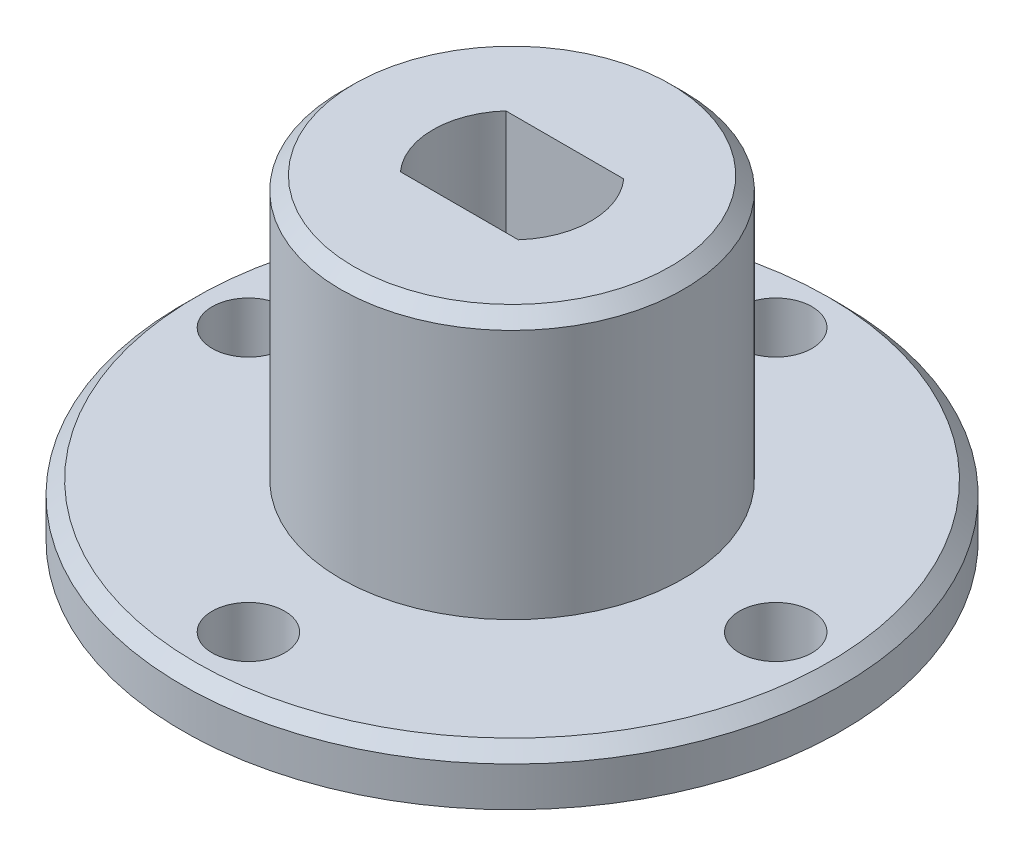
SolidWorks part; units mm, degrees
material "6061 Legierung"
ref_plane "Ebene vorne" through (0, 0, 0) normal (0, 0, 1) x (1, 0, 0)
ref_plane "Ebene oben" through (0, 0, 0) normal (0, 1, 0) x (1, 0, 0)
ref_plane "Ebene rechts" through (0, 0, 0) normal (1, 0, 0) x (0, 0, -1)
sketch "Skizze1" plane through (0, 0, 0) normal (0, 1, 0) x (1, 0, 0)
  line L0 (-4.4721, 4) -> (4.4721, 4)
  line L1 (-4.4721, -4) -> (4.4721, -4)
  circle A0 centre (0, 0) radius 13
  arc A1 (-4.4721, 4) -> (-4.4721, -4) centre (0, 0) ccw
  arc A2 (4.4721, -4) -> (4.4721, 4) centre (0, 0) ccw
  dimension "D1" = 26
  dimension "D2" = 12
  dimension "D3" = 8
  dimension "D4" = 4
extrude "Aufsatz-Linear austragen1" add sketch "Skizze1" along normal blind 20
sketch "Skizze5" plane through (0, 0, 0) normal (0, -1, 0) x (1, 0, 0)
  line L0 (4.4721, -4) -> (-4.4721, -4) construction
  line L1 (-4.4721, 4) -> (4.4721, 4) construction
  line L2 (4.4721, -4) -> (-4.4721, -4)
  line L3 (-4.4721, 4) -> (4.4721, 4)
  circle A0 centre (0, 0) radius 25
  arc A3 (4.4721, -4) -> (4.4721, 4) centre (0, 0) ccw construction
  arc A4 (-4.4721, 4) -> (-4.4721, -4) centre (0, 0) ccw construction
  arc A5 (4.4721, -4) -> (4.4721, 4) centre (0, 0) ccw
  arc A6 (-4.4721, 4) -> (-4.4721, -4) centre (0, 0) ccw
  dimension "D1" = 50
extrude "Aufsatz-Linear austragen2" add sketch "Skizze5" along normal blind 4
hole_wizard "Durchgangsloch für M51" positions "Skizze8" profile "Skizze7" hole size "M5" standard "ISO"
sketch "Skizze8" plane through (0, -4, 0) normal (0, -1, 0) x (-1, 0, 0)
  circle A0 centre (0, 0) radius 20 construction
  point P0 (0, 20)
  point P2 (20, 0)
  point P4 (0, -20)
  point P6 (-20, 0)
  dimension "D1" = 40
sketch "Skizze7" plane through (0, -4, -20) normal (1, 0, 0) x (0, 0, -1)
  line L0 (0, 0) -> (0, 26.6524)
  line L1 (0, 26.6524) -> (2.75, 25)
  line L2 (2.75, 25) -> (2.75, 0)
  line L5 (2.75, 0) -> (0, 0)
  line L10 (0, 26.6524) -> (-2.75, 25) construction
  line L11 (0, -6.35) -> (0, 107.95) construction
  dimension "Bohrerdurchmesser" = 5.5
  dimension "Bohrungstiefe" = 25
  dimension "Spitzenwinkel" = 118
chamfer "Fase1" distance 1 angle 45 2 edges at (0, 20, 13) (0, 0, -25)
